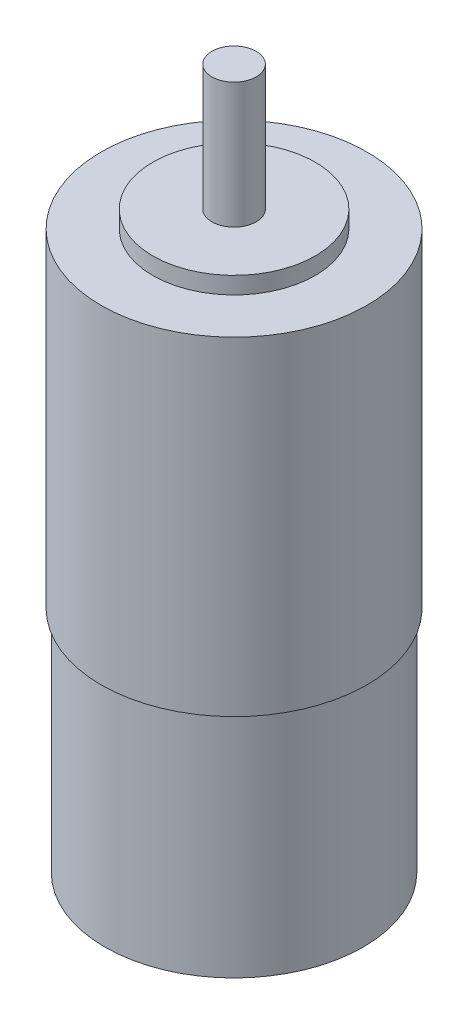
SolidWorks part; units mm, degrees
ref_plane "前视基准面" through (0, 0, 0) normal (0, 0, 1) x (1, 0, 0)
ref_plane "上视基准面" through (0, 0, 0) normal (0, 1, 0) x (1, 0, 0)
ref_plane "右视基准面" through (0, 0, 0) normal (1, 0, 0) x (0, 0, -1)
sketch "草图1" plane through (0, 0, 0) normal (0, 1, 0) x (1, 0, 0)
  circle A0 centre (0, 0) radius 17.5
  dimension "D1" = 35
extrude "凸台-拉伸1" add sketch "草图1" along normal blind 31
sketch "草图2" plane through (0, 31, 0) normal (0, 1, 0) x (1, 0, 0)
  circle A0 centre (0, 0) radius 18
  dimension "D1" = 36
extrude "凸台-拉伸2" add sketch "草图2" along normal blind 44.5
sketch "草图3" plane through (0, 75.5, 0) normal (0, 1, 0) x (1, 0, 0)
  circle A0 centre (0, 0) radius 11
  dimension "D1" = 22
extrude "凸台-拉伸3" add sketch "草图3" along normal blind 2.3
sketch "草图4" plane through (0, 77.8, 0) normal (0, 1, 0) x (1, 0, 0)
  circle A0 centre (0, 0) radius 3
  dimension "D1" = 6
extrude "凸台-拉伸4" add sketch "草图4" along normal blind 17
